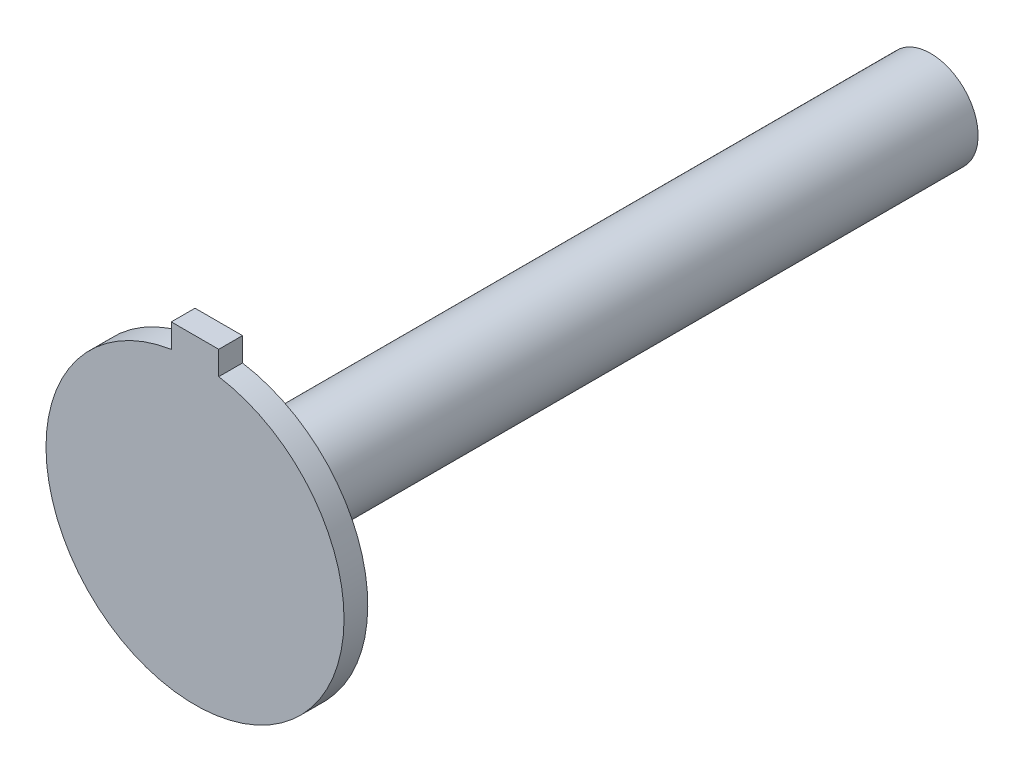
SolidWorks part; units mm, degrees
ref_plane "Plan1" through (0, 0, 0) normal (0, 0, 1) x (1, 0, 0)
ref_plane "Plan2" through (0, 0, 0) normal (0, 1, 0) x (1, 0, 0)
ref_plane "Plan3" through (0, 0, 0) normal (1, 0, 0) x (0, 0, -1)
sketch "Esquisse1" plane through (0, 0, 0) normal (0, 0, 1) x (1, 0, 0)
  line L1 (-5, 30.9994) -> (-5, 35.9994)
  line L2 (-5, 35.9994) -> (5, 35.9994)
  line L3 (5, 35.9994) -> (5, 30.9994)
  line L4 (5, 30.9994) -> (5, 33.0236) construction
  arc A0 (-5, 30.9994) -> (5, 30.9994) centre (0, 0) ccw
  arc A1 (5, -30.9994) -> (5, 30.9994) centre (0, 0) ccw construction
  dimension "D1" = 5
extrude "Base-Extrusion" add sketch "Esquisse1" along normal up to surface (5 mm away)
sketch "Esquisse2" plane through (0, 0, 0) normal (0, 0, -1) x (-1, 0, 0)
  circle A0 centre (0, 0) radius 10
  dimension "D1" = 20
extrude "Boss.-Extru.1" add sketch "Esquisse2" along normal blind 150
